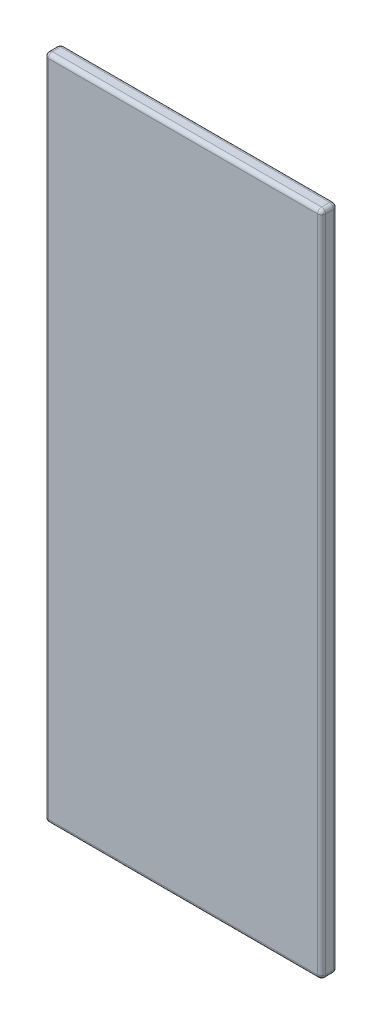
SolidWorks part; units mm, degrees
ref_plane "Front Plane" through (0, 0, 0) normal (0, 0, 1) x (1, 0, 0)
ref_plane "Top Plane" through (0, 0, 0) normal (0, 1, 0) x (1, 0, 0)
ref_plane "Right Plane" through (0, 0, 0) normal (1, 0, 0) x (0, 0, -1)
sketch "Sketch1" plane through (0, 0, 0) normal (0, 0, 1) x (1, 0, 0)
  line L1 (-17.35, -41.75) -> (17.35, -41.75)
  line L2 (-17.35, -41.75) -> (-17.35, 41.75)
  line L3 (-17.35, 41.75) -> (17.35, 41.75)
  line L4 (17.35, -41.75) -> (17.35, 41.75)
  line L5 (-17.35, -41.75) -> (17.35, 41.75) construction
  line L6 (-17.35, 41.75) -> (17.35, -41.75) construction
  point P0 (0, 0)
  dimension "D1" = 34.7
  dimension "D2" = 83.5
extrude "Boss-Extrude1" add sketch "Sketch1" along normal blind 2
fillet "Fillet1" radius 0.5 12 edges at (0, -41.75, 2) (0, -41.75, 0) (-17.35, 0, 2) (-17.35, -41.75, 1) (-17.35, 0, 0) (0, 41.75, 2) (-17.35, 41.75, 1) (0, 41.75, 0) (17.35, -41.75, 1) (17.35, 0, 2) (17.35, 41.75, 1) (17.35, 0, 0)
